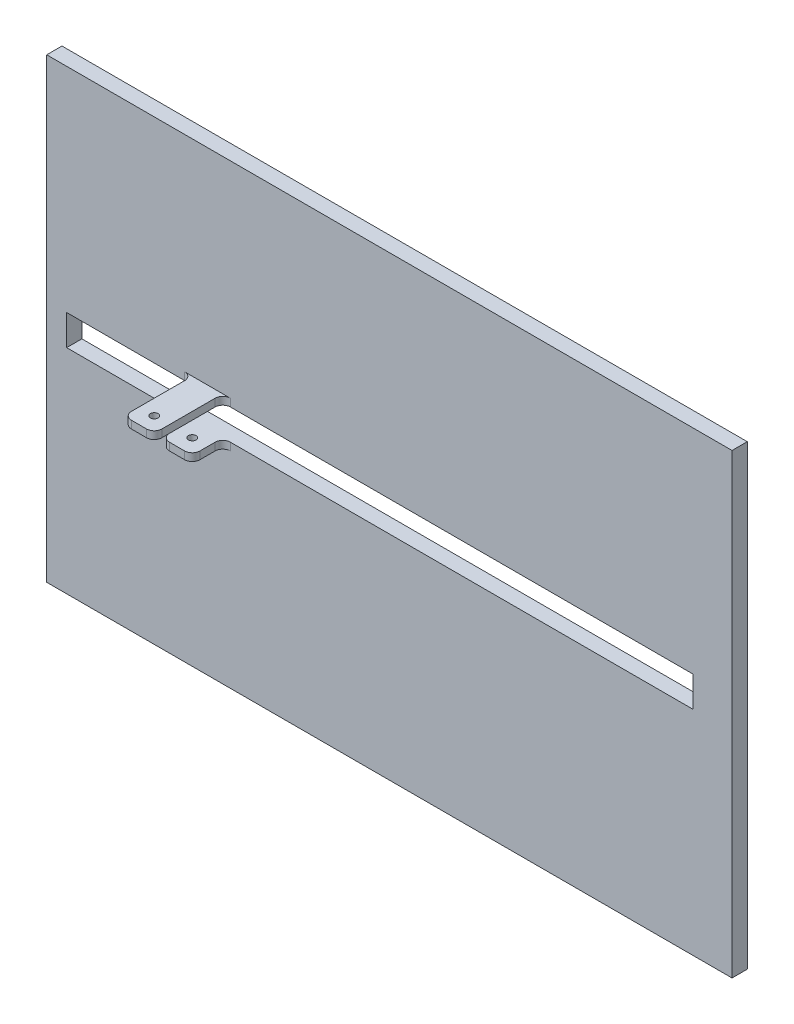
SolidWorks part; units mm, degrees
ref_plane "Front Plane" through (0, 0, 0) normal (0, 0, 1) x (1, 0, 0)
ref_plane "Top Plane" through (0, 0, 0) normal (0, 1, 0) x (1, 0, 0)
ref_plane "Right Plane" through (0, 0, 0) normal (1, 0, 0) x (0, 0, -1)
sketch "Sketch1" plane through (0, 0, 0) normal (0, 0, 1) x (1, 0, 0)
  line L1 (-650, 300) -> (650, 300)
  line L2 (-650, 300) -> (-650, -300)
  line L3 (-650, -300) -> (650, -300)
  line L4 (650, 300) -> (650, -300)
  line L5 (-650, 300) -> (650, -300) construction
  line L6 (-650, -300) -> (650, 300) construction
  line L7 (558.8382, 20) -> (-558.8382, 20)
  line L8 (558.8382, 20) -> (558.8382, -20)
  line L9 (-558.8382, 20) -> (-558.8382, -20)
  line L10 (-558.8382, -20) -> (558.8382, -20)
  point P0 (0, 0)
  point P12 (0, -20)
  dimension "D1" = 600
  dimension "D2" = 1300
extrude "Boss-Extrude1" add sketch "Sketch1" along normal blind 20
sketch "Sketch2" plane through (0, 0, 20) normal (0, 0, 1) x (1, 0, 0)
  line L1 (558.8382, 20) -> (-558.8382, 20) construction
  line L2 (-358.8382, 20) -> (-358.8382, 30)
  line L3 (-358.8382, 30) -> (-318.8382, 30)
  line L4 (-318.8382, 30) -> (-318.8382, 20)
  line L5 (-318.8382, 20) -> (-358.8382, 20)
  line L7 (-318.8382, -30) -> (-318.8382, -20)
  line L8 (-318.8382, -20) -> (-358.8382, -20)
  line L9 (-358.8382, -20) -> (-358.8382, -30)
  line L10 (-358.8382, -30) -> (-318.8382, -30)
  dimension "D1" = 10
  dimension "D2" = 40
extrude "Boss-Extrude2" add sketch "Sketch2" along normal blind 40
sketch "Sketch3" plane through (0, -30, 0) normal (0, -1, 0) x (1, 0, 0)
  circle A0 centre (-338.8382, 40) radius 5
  dimension "D1" = 10
extrude "Cut-Extrude1" cut sketch "Sketch3" against normal blind 10
sketch "Sketch4" plane through (0, 0, 60) normal (0, 0, 1) x (1, 0, 0)
  line L0 (-358.8382, 30) -> (-318.8382, 30)
  line L1 (-318.8382, 30) -> (-318.8382, 20)
  line L2 (-318.8382, 20) -> (-358.8382, 20)
  line L3 (-358.8382, 20) -> (-358.8382, 30)
extrude "Boss-Extrude3" add sketch "Sketch4" along normal blind 50
sketch "Sketch5" plane through (0, 20, 0) normal (0, -1, 0) x (1, 0, 0)
  circle A0 centre (-338.8382, 90) radius 5
  dimension "D2" = 10
extrude "Cut-Extrude2" cut sketch "Sketch5" against normal blind 10
fillet "Fillet1" radius 10 1 edges at (-318.8382, -25, 20)
fillet "Fillet2" radius 10 1 edges at (-318.8382, 25, 20)
fillet "Fillet3" radius 10 1 edges at (-358.8382, -25, 20)
fillet "Fillet4" radius 10 1 edges at (-358.8382, 25, 20)
fillet "Fillet5" radius 10 1 edges at (-318.8382, -25, 60)
fillet "Fillet6" radius 10 1 edges at (-358.8382, -25, 60)
fillet "Fillet7" radius 10 1 edges at (-358.8382, 25, 110)
fillet "Fillet8" radius 10 1 edges at (-318.8382, 25, 110)
sketch "Sketch6" plane through (558.8382, 0, 0) normal (-1, 0, 0) x (0, 0, 1)
  line L0 (0, 20) -> (20, 20)
  line L1 (20, 20) -> (20, -20)
  line L2 (20, -20) -> (0, -20)
  line L3 (0, 300) -> (0, -300) construction
  line L4 (0, -20) -> (0, 20)
extrude "Boss-Extrude4" add sketch "Sketch6" along normal blind 260
sketch "Sketch7" plane through (-558.8382, 0, 0) normal (1, 0, 0) x (0, 0, -1)
  line L0 (-20, 20) -> (0, 20)
  line L1 (0, 20) -> (0, -20)
  line L2 (0, -20) -> (-20, -20)
  line L3 (-20, -20) -> (-20, 20)
extrude "Boss-Extrude5" add sketch "Sketch7" along normal blind 35
sketch "Sketch8" plane through (-650, 0, 0) normal (-1, 0, 0) x (0, 0, 1)
  line L0 (20, 300) -> (20, -300)
  line L1 (20, -300) -> (0, -300)
  line L2 (0, -300) -> (0, 300)
  line L3 (0, 300) -> (20, 300)
extrude "Cut-Extrude3" cut sketch "Sketch8" against normal blind 100
sketch "Sketch9" plane through (650, 0, 0) normal (1, 0, 0) x (0, 0, -1)
  line L0 (-20, -300) -> (-20, 300)
  line L1 (-20, 300) -> (0, 300)
  line L2 (0, 300) -> (0, -300)
  line L3 (0, -300) -> (-20, -300)
extrude "Cut-Extrude4" cut sketch "Sketch9" against normal blind 300
